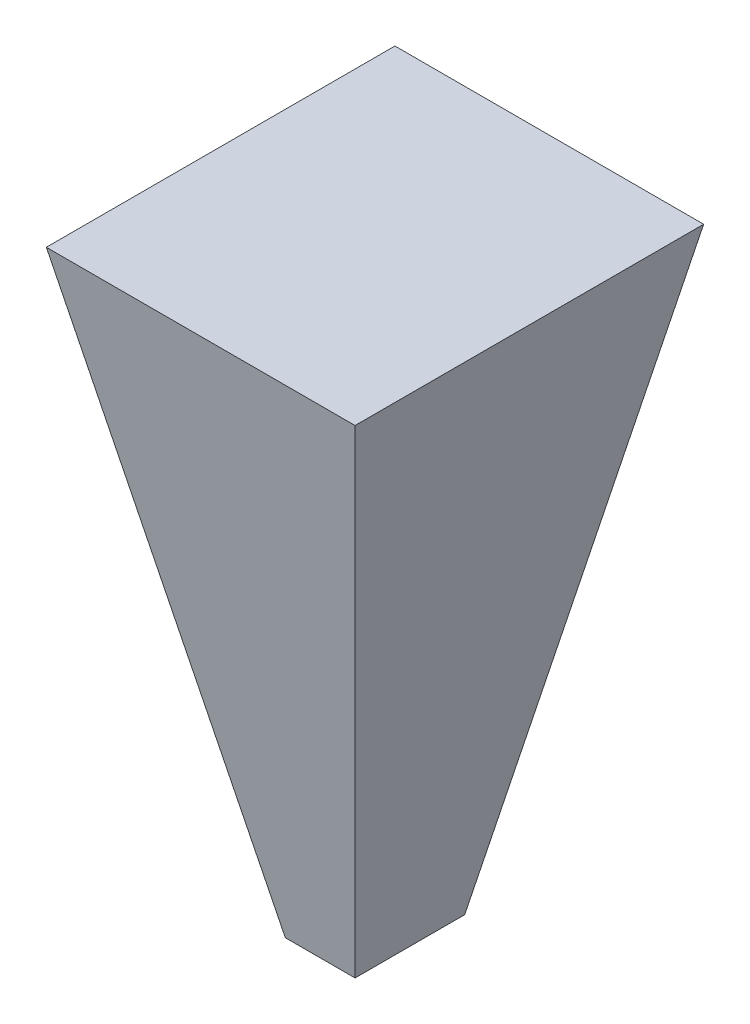
SolidWorks part; units mm, degrees
ref_plane "Front Plane" through (0, 0, 0) normal (0, 0, 1) x (1, 0, 0)
ref_plane "Top Plane" through (0, 0, 0) normal (0, 1, 0) x (1, 0, 0)
ref_plane "Right Plane" through (0, 0, 0) normal (1, 0, 0) x (0, 0, -1)
sketch "Sketch1" plane through (0, 0, 0) normal (0, 1, 0) x (1, 0, 0)
  line L1 (-3.5, 5.5) -> (3.5, 5.5)
  line L2 (-3.5, 5.5) -> (-3.5, -5.5)
  line L3 (-3.5, -5.5) -> (3.5, -5.5)
  line L4 (3.5, 5.5) -> (3.5, -5.5)
  line L5 (-3.5, 5.5) -> (3.5, -5.5) construction
  line L6 (-3.5, -5.5) -> (3.5, 5.5) construction
  point P0 (0, 0)
  dimension "D1" = 7
  dimension "D2" = 11
extrude "Boss-Extrude1" add sketch "Sketch1" along normal blind 60 draft 11.3
